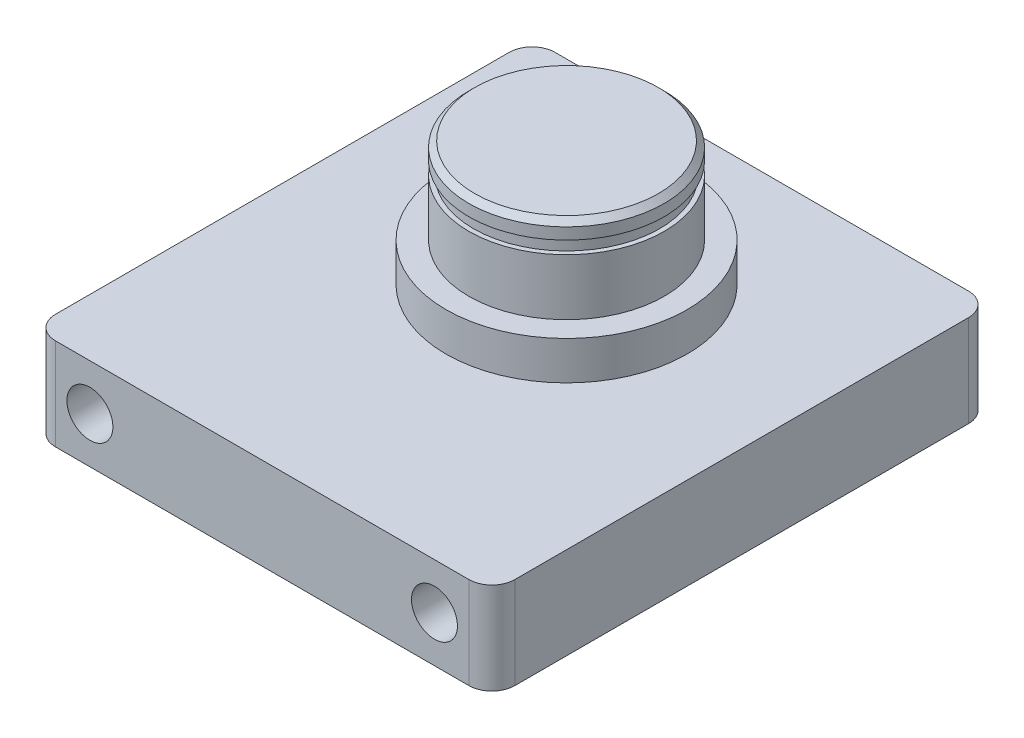
SolidWorks part; units mm, degrees
material "1023 碳钢板 (SS)"
ref_plane "前视基准面" through (0, 0, 0) normal (0, 0, 1) x (1, 0, 0)
ref_plane "上视基准面" through (0, 0, 0) normal (0, 1, 0) x (1, 0, 0)
ref_plane "右视基准面" through (0, 0, 0) normal (1, 0, 0) x (0, 0, -1)
sketch "草图1" plane through (0, 0, 0) normal (0, 1, 0) x (1, 0, 0)
  line L1 (-20, -26.5) -> (20, -26.5)
  line L2 (-20, -26.5) -> (-20, 17)
  line L3 (-20, 17) -> (20, 17)
  line L4 (20, -26.5) -> (20, 17)
  line L5 (-20, -26.5) -> (20, 17) construction
  line L6 (-20, 17) -> (20, -26.5) construction
  point P0 (0, 0)
  dimension "D1" = 43.5
  dimension "D2" = 40
  dimension "D3" = 17
extrude "凸台-拉伸1" add sketch "草图1" along normal blind 8
sketch "草图2" plane through (0, 8, 0) normal (0, 1, 0) x (1, 0, 0)
  circle A0 centre (0, 0) radius 10.5
  dimension "D1" = 21
extrude "凸台-拉伸2" add sketch "草图2" along normal blind 3.35
sketch "草图3" plane through (0, 11.35, 0) normal (0, 1, 0) x (1, 0, 0)
  circle A0 centre (0, 0) radius 8.5
  dimension "D1" = 17
extrude "凸台-拉伸3" add sketch "草图3" along normal blind 7.5
sketch "草图4" plane through (0, 0, -17) normal (0, 0, -1) x (-1, 0, 0)
  line L0 (-1020, 4) -> (48980, 4) construction
  line L1 (-20, 8) -> (-20, 0) construction
  circle A0 centre (-15, 4) radius 2
  circle A1 centre (15, 4) radius 2
  point P5 (-20, 4)
  dimension "D1" = 4
  dimension "D2" = 15
  dimension "D3" = 15
extrude "切除-拉伸1" cut sketch "草图4" against normal through all
ref_plane "基准面1" through (0, 17.35, 0) normal (0, 1, 0) x (1, 0, 0)
sketch "草图5" plane through (0, 17.35, 0) normal (0, 1, 0) x (1, 0, 0)
  circle A0 centre (0, 0) radius 8.5
  circle A1 centre (0, 0) radius 8.1
  dimension "D1" = 17
  dimension "D2" = 0.4
extrude "切除-拉伸2" cut sketch "草图5" against normal blind 1.1
chamfer "倒角1" distance 0.5 angle 45 1 edges at (0, 18.85, 8.5)
fillet "圆角1" radius 2 4 edges at (20, 4, -17) (20, 4, 26.5) (-20, 4, 26.5) (-20, 4, -17)
